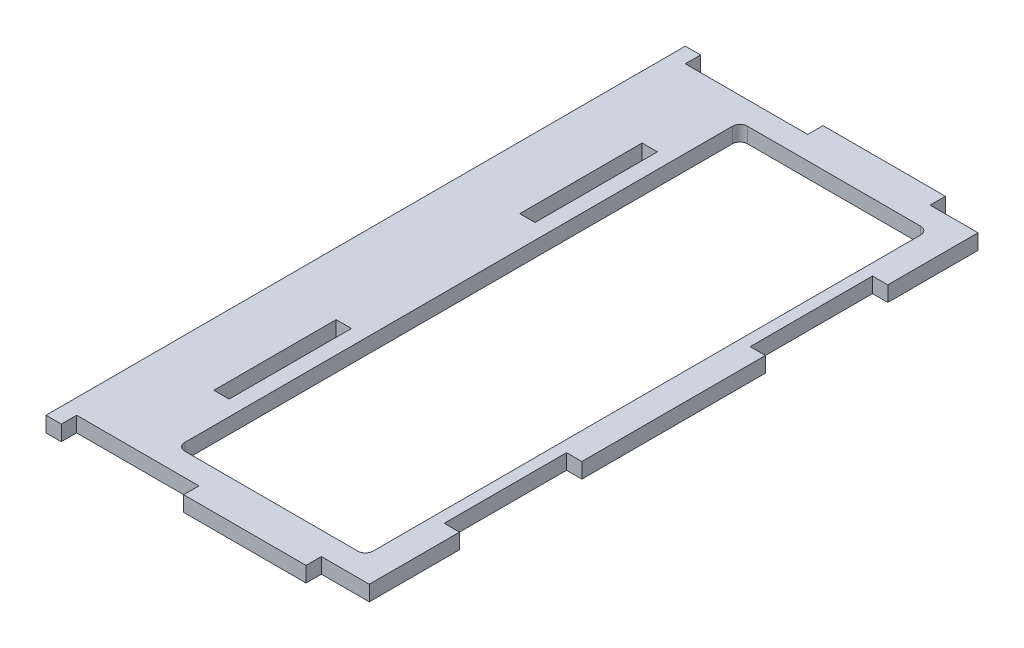
SolidWorks part; units mm, degrees
material "Acrylic (Medium-high impact)"
ref_plane "Front Plane" through (0, 0, 0) normal (0, 0, 1) x (1, 0, 0)
ref_plane "Top Plane" through (0, 0, 0) normal (0, 1, 0) x (1, 0, 0)
ref_plane "Right Plane" through (0, 0, 0) normal (1, 0, 0) x (0, 0, -1)
sketch "Sketch2" plane through (0, 0, 0) normal (0, 1, 0) x (1, 0, 0)
  line L0 (-147.5, 0) -> (147.5, 0) construction
  line L5 (-185, 195.2) -> (185, 195.2) construction
  line L6 (-197.7, -132.7) -> (197.7, -132.7)
  line L13 (110, 120) -> (185, 120)
  line L14 (110, 120) -> (110, -120)
  line L15 (110, -120) -> (185, -120)
  line L16 (185, 120) -> (185, -120)
  line L17 (110, 120) -> (185, -120) construction
  line L18 (110, -120) -> (185, 120) construction
  line L19 (-185, 120) -> (-110, 120)
  line L20 (-185, 120) -> (-185, -120)
  line L21 (-185, -120) -> (-110, -120)
  line L22 (-110, 120) -> (-110, -120)
  line L23 (-185, 120) -> (-110, -120) construction
  line L24 (-185, -120) -> (-110, 120) construction
  line L26 (-110, -37.5) -> (110, -37.5)
  line L27 (-110, -37.5) -> (-110, 37.5)
  line L28 (-110, 37.5) -> (110, 37.5)
  line L29 (110, -37.5) -> (110, 37.5)
  line L30 (-110, -37.5) -> (110, 37.5) construction
  line L31 (-110, 37.5) -> (110, -37.5) construction
  line L41 (-197.7, -132.7) -> (-197.7, 132.7)
  line L42 (-185, 132.7) -> (185, 132.7) construction
  line L43 (197.7, -132.7) -> (197.7, 132.7)
  line L44 (-197.7, -132.7) -> (197.7, 132.7) construction
  line L45 (-197.7, 132.7) -> (197.7, -132.7) construction
  line L47 (-197.7, 132.7) -> (-197.7, 257.7)
  line L48 (-197.7, 257.7) -> (-185, 257.7)
  line L49 (-185, 132.7) -> (-185, 257.7)
  line L51 (185, 132.7) -> (185, 257.7)
  line L52 (185, 257.7) -> (197.7, 257.7)
  line L53 (197.7, 132.7) -> (197.7, 257.7)
  line L54 (-185, 132.7) -> (185, 132.7)
  line L55 (223.1, 132.7) -> (223.1, 283.1)
  line L56 (159.6, 283.1) -> (223.1, 283.1)
  line L57 (159.6, 158.1) -> (159.6, 283.1)
  line L58 (-159.6, 158.1) -> (159.6, 158.1)
  line L59 (-159.6, 158.1) -> (-159.6, 283.1)
  line L60 (-223.1, 283.1) -> (-159.6, 283.1)
  line L61 (-223.1, 132.7) -> (-223.1, 283.1)
  line L62 (-223.1, -158.1) -> (-223.1, 132.7)
  line L63 (-223.1, -158.1) -> (223.1, -158.1)
  line L64 (223.1, -158.1) -> (223.1, 132.7)
  circle A0 centre (0, 308.1) radius 150
  point P2 (0, 0)
  point P13 (147.5, 0)
  point P18 (-147.5, 0)
  point P23 (0, 0)
  point P24 (0, 0)
  point P35 (0, 195.2)
  dimension "D1" = 300
  dimension "D2" = 75
  dimension "D3" = 240
  dimension "D4" = 75
  dimension "D5" = 220
  dimension "D6" = 12.7
  dimension "D7" = 12.7
  dimension "D8" = 12.7
  dimension "D9" = 125
  dimension "D10" = 25.4
sketch "Sketch5" plane through (0, 0, 0) normal (0, 1, 0) x (1, 0, 0)
  line L1 (197.7, -132.7) -> (-197.7, -132.7)
  line L2 (197.7, -132.7) -> (197.7, 132.7)
  line L3 (197.7, 132.7) -> (-197.7, 132.7)
  line L4 (-197.7, -132.7) -> (-197.7, 132.7)
extrude "Boss-Extrude3" add sketch "Sketch5" along normal blind 6.35
sketch "Sketch6" plane through (0, 6.35, 0) normal (0, 1, 0) x (1, 0, 0)
  line L0 (-185, 120) -> (-110, 120) construction
  line L1 (-185, 120) -> (-185, -120) construction
  line L2 (-185, -120) -> (-110, -120) construction
  line L3 (-110, 120) -> (-110, -120) construction
  line L4 (110, 120) -> (110, -120) construction
  line L5 (110, 120) -> (185, 120) construction
  line L6 (185, 120) -> (185, -120) construction
  line L7 (110, -120) -> (185, -120) construction
  line L8 (-185, 120) -> (-110, 120)
  line L9 (-185, 120) -> (-185, -120)
  line L10 (-185, -120) -> (-110, -120)
  line L11 (-110, 120) -> (-110, -120)
  line L12 (110, 120) -> (110, -120)
  line L13 (110, 120) -> (185, 120)
  line L14 (185, 120) -> (185, -120)
  line L15 (110, -120) -> (185, -120)
  line L16 (108.4125, 121.5875) -> (108.4125, -121.5875)
  line L17 (108.4125, -121.5875) -> (186.5875, -121.5875)
  line L18 (186.5875, 121.5875) -> (186.5875, -121.5875)
  line L19 (108.4125, 121.5875) -> (186.5875, 121.5875)
  line L20 (-108.4125, 121.5875) -> (-108.4125, -121.5875)
  line L21 (-186.5875, -121.5875) -> (-108.4125, -121.5875)
  line L22 (-186.5875, 121.5875) -> (-186.5875, -121.5875)
  line L23 (-186.5875, 121.5875) -> (-108.4125, 121.5875)
  dimension "D1" = 1.5875
extrude "Cut-Extrude1" cut sketch "Sketch6" against normal blind 6.35 contours L12 L15 L14 L13 | L19 L16 L17 L18 L15 L12 L13 L14 | L11 L8 L9 L10 | L23 L22 L21 L20 L8 L11 L10 L9
sketch "Sketch7" [suppressed] plane through (0, 6.35, 0) normal (0, 1, 0) x (1, 0, 0)
  arc A0 (191.675, -14.35) -> (191.043, -17.5242) centre (191.675, -16) ccw construction
  arc A1 (192.307, -14.4758) -> (191.675, -14.35) centre (191.675, -16) ccw construction
  arc A2 (191.675, -17.65) -> (192.307, -14.4758) centre (191.675, -16) ccw construction
  arc A3 (191.043, -17.5242) -> (191.675, -17.65) centre (191.675, -16) ccw construction
  arc A4 (191.675, 17.65) -> (191.043, 14.4758) centre (191.675, 16) ccw construction
  arc A5 (192.307, 17.5242) -> (191.675, 17.65) centre (191.675, 16) ccw construction
  arc A6 (191.675, 14.35) -> (192.307, 17.5242) centre (191.675, 16) ccw construction
  arc A7 (191.043, 14.4758) -> (191.675, 14.35) centre (191.675, 16) ccw construction
  arc A8 (103.325, -14.35) -> (102.693, -17.5242) centre (103.325, -16) ccw construction
  arc A9 (103.957, -14.4758) -> (103.325, -14.35) centre (103.325, -16) ccw construction
  arc A10 (103.325, -17.65) -> (103.957, -14.4758) centre (103.325, -16) ccw construction
  arc A11 (102.693, -17.5242) -> (103.325, -17.65) centre (103.325, -16) ccw construction
  arc A12 (103.325, 17.65) -> (102.693, 14.4758) centre (103.325, 16) ccw construction
  arc A13 (103.957, 17.5242) -> (103.325, 17.65) centre (103.325, 16) ccw construction
  arc A14 (103.325, 14.35) -> (103.957, 17.5242) centre (103.325, 16) ccw construction
  arc A15 (102.693, 14.4758) -> (103.325, 14.35) centre (103.325, 16) ccw construction
  arc A16 (-103.325, 17.65) -> (-103.957, 14.4758) centre (-103.325, 16) ccw construction
  arc A17 (-102.693, 17.5242) -> (-103.325, 17.65) centre (-103.325, 16) ccw construction
  arc A18 (-103.325, 14.35) -> (-102.693, 17.5242) centre (-103.325, 16) ccw construction
  arc A19 (-103.957, 14.4758) -> (-103.325, 14.35) centre (-103.325, 16) ccw construction
  arc A20 (-103.325, -14.35) -> (-103.957, -17.5242) centre (-103.325, -16) ccw construction
  arc A21 (-102.693, -14.4758) -> (-103.325, -14.35) centre (-103.325, -16) ccw construction
  arc A22 (-103.325, -17.65) -> (-102.693, -14.4758) centre (-103.325, -16) ccw construction
  arc A23 (-103.957, -17.5242) -> (-103.325, -17.65) centre (-103.325, -16) ccw construction
  arc A24 (-191.675, -14.35) -> (-192.307, -17.5242) centre (-191.675, -16) ccw construction
  arc A25 (-191.043, -14.4758) -> (-191.675, -14.35) centre (-191.675, -16) ccw construction
  arc A26 (-191.675, -17.65) -> (-191.043, -14.4758) centre (-191.675, -16) ccw construction
  arc A27 (-192.307, -17.5242) -> (-191.675, -17.65) centre (-191.675, -16) ccw construction
  arc A28 (-191.675, 14.35) -> (-191.043, 17.5242) centre (-191.675, 16) ccw construction
  arc A29 (-192.307, 14.4758) -> (-191.675, 14.35) centre (-191.675, 16) ccw construction
  arc A30 (-191.675, 17.65) -> (-192.307, 14.4758) centre (-191.675, 16) ccw construction
  arc A31 (-191.043, 17.5242) -> (-191.675, 17.65) centre (-191.675, 16) ccw construction
  circle A32 centre (-61.175, -10) radius 2.25 construction
  circle A33 centre (-61.175, 22) radius 2.25 construction
  circle A34 centre (61.175, 22) radius 2.25 construction
  circle A35 centre (61.175, -10) radius 2.25 construction
  arc A36 (191.675, -14.35) -> (191.043, -17.5242) centre (191.675, -16) ccw construction
  arc A37 (192.307, -14.4758) -> (191.675, -14.35) centre (191.675, -16) ccw construction
  arc A38 (191.675, -17.65) -> (192.307, -14.4758) centre (191.675, -16) ccw construction
  arc A39 (191.043, -17.5242) -> (191.675, -17.65) centre (191.675, -16) ccw construction
  arc A40 (191.675, 17.65) -> (191.043, 14.4758) centre (191.675, 16) ccw construction
  arc A41 (192.307, 17.5242) -> (191.675, 17.65) centre (191.675, 16) ccw construction
  arc A42 (191.675, 14.35) -> (192.307, 17.5242) centre (191.675, 16) ccw construction
  arc A43 (191.043, 14.4758) -> (191.675, 14.35) centre (191.675, 16) ccw construction
  arc A44 (103.325, -14.35) -> (102.693, -17.5242) centre (103.325, -16) ccw construction
  arc A45 (103.957, -14.4758) -> (103.325, -14.35) centre (103.325, -16) ccw construction
  arc A46 (103.325, -17.65) -> (103.957, -14.4758) centre (103.325, -16) ccw construction
  arc A47 (102.693, -17.5242) -> (103.325, -17.65) centre (103.325, -16) ccw construction
  arc A48 (103.325, 17.65) -> (102.693, 14.4758) centre (103.325, 16) ccw construction
  arc A49 (103.957, 17.5242) -> (103.325, 17.65) centre (103.325, 16) ccw construction
  arc A50 (103.325, 14.35) -> (103.957, 17.5242) centre (103.325, 16) ccw construction
  arc A51 (102.693, 14.4758) -> (103.325, 14.35) centre (103.325, 16) ccw construction
  arc A52 (-103.325, 17.65) -> (-103.957, 14.4758) centre (-103.325, 16) ccw construction
  arc A53 (-102.693, 17.5242) -> (-103.325, 17.65) centre (-103.325, 16) ccw construction
  arc A54 (-103.325, 14.35) -> (-102.693, 17.5242) centre (-103.325, 16) ccw construction
  arc A55 (-103.957, 14.4758) -> (-103.325, 14.35) centre (-103.325, 16) ccw construction
  arc A56 (-103.325, -14.35) -> (-103.957, -17.5242) centre (-103.325, -16) ccw construction
  arc A57 (-102.693, -14.4758) -> (-103.325, -14.35) centre (-103.325, -16) ccw construction
  arc A58 (-103.325, -17.65) -> (-102.693, -14.4758) centre (-103.325, -16) ccw construction
  arc A59 (-103.957, -17.5242) -> (-103.325, -17.65) centre (-103.325, -16) ccw construction
  arc A60 (-191.675, -14.35) -> (-192.307, -17.5242) centre (-191.675, -16) ccw construction
  arc A61 (-191.043, -14.4758) -> (-191.675, -14.35) centre (-191.675, -16) ccw construction
  arc A62 (-191.675, -17.65) -> (-191.043, -14.4758) centre (-191.675, -16) ccw construction
  arc A63 (-192.307, -17.5242) -> (-191.675, -17.65) centre (-191.675, -16) ccw construction
  arc A64 (-191.675, 14.35) -> (-191.043, 17.5242) centre (-191.675, 16) ccw construction
  arc A65 (-192.307, 14.4758) -> (-191.675, 14.35) centre (-191.675, 16) ccw construction
  arc A66 (-191.675, 17.65) -> (-192.307, 14.4758) centre (-191.675, 16) ccw construction
  arc A67 (-191.043, 17.5242) -> (-191.675, 17.65) centre (-191.675, 16) ccw construction
  circle A68 centre (-61.175, -10) radius 2.25 construction
  circle A69 centre (-61.175, 22) radius 2.25 construction
  circle A70 centre (61.175, 22) radius 2.25 construction
  circle A71 centre (61.175, -10) radius 2.25 construction
hole_wizard "Ø4.0mm Dowel Hole1" [suppressed] positions "Sketch8" profile "Sketch9" hole size "Ø4.0" standard "ANSI Metric"
sketch "Sketch8" [suppressed] plane through (0, 6.35, 0) normal (0, 1, 0) x (1, 0, 0)
  point P0 (191.675, -16)
  point P3 (191.675, 16)
  point P6 (103.325, -16)
  point P9 (103.325, 16)
  point P12 (-191.675, -16)
  point P15 (-191.675, 16)
  point P18 (-103.325, -16)
  point P21 (-103.325, 16)
  point P24 (-61.175, -10)
  point P27 (-61.175, 22)
  point P30 (61.175, 22)
  point P33 (61.175, -10)
sketch "Sketch9" plane through (191.675, 6.35, 16) normal (1, 0, 0) x (0, 0, 1)
  line L0 (0, 0) -> (0, 6.35)
  line L1 (0, 6.35) -> (2.25, 6.35)
  line L2 (2.25, 6.35) -> (2.25, 0)
  line L5 (2.25, 0) -> (0, 0)
  line L11 (0, -6.35) -> (0, 107.95) construction
  dimension "Thru Hole Dia." = 4.5
  dimension "Thru Hole Depth" = 6.35
sketch "Sketch10" plane through (0, 0, 0) normal (0, -1, 0) x (1, 0, 0)
  line L0 (-191.35, -126.35) -> (191.35, -126.35)
  line L1 (191.35, -126.35) -> (191.35, 126.35)
  line L2 (191.35, 126.35) -> (-191.35, 126.35)
  line L3 (-191.35, 126.35) -> (-191.35, -126.35)
  line L4 (197.7, -132.7) -> (197.7, 132.7)
  line L5 (197.7, 132.7) -> (-197.7, 132.7)
  line L6 (-197.7, 132.7) -> (-197.7, -132.7)
  line L7 (-197.7, -132.7) -> (197.7, -132.7)
  line L8 (197.7, -132.7) -> (197.7, 132.7)
  line L9 (197.7, 132.7) -> (-197.7, 132.7)
  line L10 (-197.7, 132.7) -> (-197.7, -132.7)
  line L11 (-197.7, -132.7) -> (197.7, -132.7)
  line L12 (102.0625, -126.35) -> (102.0625, 126.35)
  line L13 (-102.0625, -126.35) -> (-102.0625, 126.35)
  line L14 (108.4125, -126.35) -> (108.4125, 126.35)
  line L15 (-108.4125, -126.35) -> (-108.4125, 126.35)
  line L16 (108.4125, -121.5875) -> (108.4125, 121.5875) construction
  line L17 (-108.4125, -121.5875) -> (-108.4125, 121.5875) construction
  line L18 (95.7125, -126.35) -> (95.7125, 126.35)
  line L19 (-95.7125, -126.35) -> (-95.7125, 126.35)
  line L20 (197.7, 0) -> (-197.7, 0) construction
  line L21 (102.0625, -88.9) -> (95.7125, -88.9)
  line L22 (102.0625, -88.9) -> (102.0625, -38.1)
  line L23 (102.0625, -38.1) -> (95.7125, -38.1)
  line L24 (95.7125, -88.9) -> (95.7125, -38.1)
  line L25 (102.0625, 38.1) -> (95.7125, 38.1)
  line L26 (102.0625, 38.1) -> (102.0625, 88.9)
  line L27 (102.0625, 88.9) -> (95.7125, 88.9)
  line L28 (95.7125, 38.1) -> (95.7125, 88.9)
  line L29 (-102.0625, -88.9) -> (-95.7125, -88.9)
  line L30 (-102.0625, -88.9) -> (-102.0625, -38.1)
  line L31 (-102.0625, -38.1) -> (-95.7125, -38.1)
  line L32 (-95.7125, -88.9) -> (-95.7125, -38.1)
  line L33 (-95.7125, 88.9) -> (-102.0625, 88.9)
  line L34 (-95.7125, 88.9) -> (-95.7125, 38.1)
  line L35 (-95.7125, 38.1) -> (-102.0625, 38.1)
  line L36 (-102.0625, 88.9) -> (-102.0625, 38.1)
  line L37 (76.2, 126.35) -> (25.4, 126.35)
  line L38 (76.2, 126.35) -> (76.2, 132.7)
  line L39 (76.2, 132.7) -> (25.4, 132.7)
  line L40 (25.4, 126.35) -> (25.4, 132.7)
  line L41 (-25.4, 126.35) -> (-76.2, 126.35)
  line L42 (-25.4, 126.35) -> (-25.4, 132.7)
  line L43 (-25.4, 132.7) -> (-76.2, 132.7)
  line L44 (-76.2, 126.35) -> (-76.2, 132.7)
  line L45 (177.8, 126.35) -> (127, 126.35)
  line L46 (177.8, 126.35) -> (177.8, 132.7)
  line L47 (177.8, 132.7) -> (127, 132.7)
  line L48 (127, 126.35) -> (127, 132.7)
  line L49 (-127, 126.35) -> (-177.8, 126.35)
  line L50 (-127, 126.35) -> (-127, 132.7)
  line L51 (-127, 132.7) -> (-177.8, 132.7)
  line L52 (-177.8, 126.35) -> (-177.8, 132.7)
  line L53 (-127, -132.7) -> (-177.8, -132.7)
  line L54 (-177.8, -126.35) -> (-177.8, -132.7)
  line L55 (-127, -126.35) -> (-177.8, -126.35)
  line L56 (-127, -126.35) -> (-127, -132.7)
  line L57 (-25.4, -132.7) -> (-76.2, -132.7)
  line L58 (-76.2, -126.35) -> (-76.2, -132.7)
  line L59 (-25.4, -126.35) -> (-76.2, -126.35)
  line L60 (-25.4, -126.35) -> (-25.4, -132.7)
  line L61 (76.2, -132.7) -> (25.4, -132.7)
  line L62 (25.4, -126.35) -> (25.4, -132.7)
  line L63 (76.2, -126.35) -> (25.4, -126.35)
  line L64 (76.2, -126.35) -> (76.2, -132.7)
  line L65 (177.8, -132.7) -> (127, -132.7)
  line L66 (127, -126.35) -> (127, -132.7)
  line L67 (177.8, -126.35) -> (127, -126.35)
  line L68 (177.8, -126.35) -> (177.8, -132.7)
  line L69 (191.35, 126.35) -> (197.7, 126.35)
  line L70 (-191.35, 126.35) -> (-197.7, 126.35)
  line L71 (-191.35, -126.35) -> (-197.7, -126.35)
  line L72 (191.35, -126.35) -> (197.7, -126.35)
  line M31 (197.7, -132.7) -> (197.7, 132.7)
  line M32 (197.7, 132.7) -> (-197.7, 132.7)
  line M33 (-197.7, 132.7) -> (-197.7, -132.7)
  line M34 (-197.7, -132.7) -> (197.7, -132.7)
  dimension "D3" = 6.35
  dimension "D4" = 6.35
  dimension "D5" = 6.35
  dimension "D6" = 6.35
  dimension "D7" = 50.8
  dimension "D8" = 50.8
  dimension "D9" = 76.2
  dimension "D10" = 38.1
  dimension "D11" = 50.8
  dimension "D12" = 50.8
  dimension "D13" = 50.8
  dimension "D14" = 25.4
  dimension "D15" = 50.8
  dimension "D16" = 50.8
  dimension "D17" = 50.8
  dimension "D18" = 50.8
  dimension "D1" = 0
  dimension "D2" = 6.35
extrude "Cut-Extrude2" cut sketch "Sketch10" against normal blind 6.35 contours L12 L23 L18 L21 | L12 L27 L18 L25 | L35 L19 L33 L13 | L31 L13 L29 L19 | L2 L69 L8 L46 M32 | L2 L48 L38 M32 | L42 L2 L40 M32 | L50 L2 L44 M32 | L70 L2 L52 M32 M33 | L0 L71 L54 M33 M34 | L58 L0 L56 M34 | L62 L0 L60 M34 | L66 L0 L64 M34 | L72 L0 L68 M34 M31
sketch "Sketch11" plane through (197.7, 0, 0) normal (1, 0, 0) x (0, 0, -1)
  line L0 (-88.9, 0) -> (-38.1, 0) construction
  line L1 (-38.1, 0) -> (-38.1, 6.35) construction
  line L2 (-38.1, 6.35) -> (-88.9, 6.35) construction
  line L3 (-88.9, 6.35) -> (-88.9, 0) construction
  line L4 (38.1, 0) -> (88.9, 0) construction
  line L5 (88.9, 0) -> (88.9, 6.35) construction
  line L6 (88.9, 6.35) -> (38.1, 6.35) construction
  line L7 (38.1, 6.35) -> (38.1, 0) construction
  line L8 (-88.9, 0) -> (-38.1, 0)
  line L9 (-38.1, 0) -> (-38.1, 6.35)
  line L10 (-38.1, 6.35) -> (-88.9, 6.35)
  line L11 (-88.9, 6.35) -> (-88.9, 0)
  line L12 (38.1, 0) -> (88.9, 0)
  line L13 (88.9, 0) -> (88.9, 6.35)
  line L14 (88.9, 6.35) -> (38.1, 6.35)
  line L15 (38.1, 6.35) -> (38.1, 0)
extrude "Cut-Extrude3" cut sketch "Sketch11" against normal blind 6.35
mirror "Mirror1" about plane through (0, 0, 0) normal (1, 0, 0) of "Cut-Extrude3"
sketch "Sketch12" plane through (0, 0, 0) normal (0, -1, 0) x (1, 0, 0)
  line L0 (108.4125, -121.5875) -> (108.4125, 121.5875) construction
  line L1 (186.5875, -121.5875) -> (108.4125, -121.5875)
  line L2 (186.5875, -121.5875) -> (186.5875, -116.825)
  line L3 (186.5875, -116.825) -> (108.4125, -116.825)
  line L4 (108.4125, -121.5875) -> (108.4125, -116.825)
  line L5 (186.5875, -121.5875) -> (186.5875, 121.5875) construction
  line L6 (108.4125, 121.5875) -> (186.5875, 121.5875)
  line L7 (108.4125, 121.5875) -> (108.4125, 116.825)
  line L8 (108.4125, 116.825) -> (186.5875, 116.825)
  line L9 (186.5875, 121.5875) -> (186.5875, 116.825)
  line L10 (-186.5875, -121.5875) -> (-186.5875, 121.5875) construction
  line L11 (-108.4125, 121.5875) -> (-186.5875, 121.5875)
  line L12 (-108.4125, 121.5875) -> (-108.4125, 116.825)
  line L13 (-108.4125, 116.825) -> (-186.5875, 116.825)
  line L14 (-186.5875, 121.5875) -> (-186.5875, 116.825)
  line L15 (-108.4125, -121.5875) -> (-108.4125, 121.5875) construction
  line L16 (-186.5875, -121.5875) -> (-108.4125, -121.5875)
  line L17 (-186.5875, -121.5875) -> (-186.5875, -116.825)
  line L18 (-186.5875, -116.825) -> (-108.4125, -116.825)
  line L19 (-108.4125, -121.5875) -> (-108.4125, -116.825)
  dimension "D1" = 4.7625
extrude "Boss-Extrude4" add sketch "Sketch12" against normal up to surface (6.35 mm away) up to face at (98.8875, 6.35, 63.5)
fillet "Fillet1" radius 3.175 8 edges at (-186.5875, 3.175, 116.825) (-108.4125, 3.175, 116.825) (-186.5875, 3.175, -116.825) (-108.4125, 3.175, -116.825) (108.4125, 3.175, 116.825) (186.5875, 3.175, 116.825) (108.4125, 3.175, -116.825) (186.5875, 3.175, -116.825)
sketch "Sketch13" plane through (0, 0, 0) normal (0, -1, 0) x (1, 0, 0)
  line L1 (69.85, -132.7) -> (-69.85, -132.7)
  line L2 (69.85, -132.7) -> (69.85, 132.7)
  line L3 (69.85, 132.7) -> (-69.85, 132.7)
  line L4 (-69.85, -132.7) -> (-69.85, 132.7)
  line L56 (-197.7, 88.9) -> (-191.35, 88.9)
  line L57 (-191.35, 88.9) -> (-191.35, 38.1)
  line L58 (-191.35, 38.1) -> (-197.7, 38.1)
  line L59 (-197.7, 38.1) -> (-197.7, -38.1)
  line L60 (-197.7, -38.1) -> (-191.35, -38.1)
  line L61 (-191.35, -38.1) -> (-191.35, -88.9)
  line L62 (-191.35, -88.9) -> (-197.7, -88.9)
  line L63 (-197.7, -88.9) -> (-197.7, -126.35)
  line L64 (-197.7, -126.35) -> (-177.8, -126.35)
  line L65 (-177.8, -126.35) -> (-177.8, -132.7)
  line L66 (-177.8, -132.7) -> (-127, -132.7)
  line L67 (-127, -132.7) -> (-127, -126.35)
  line L68 (-127, -126.35) -> (-76.2, -126.35)
  line L69 (-76.2, -126.35) -> (-76.2, -132.7)
  line L70 (-76.2, -132.7) -> (-25.4, -132.7)
  line L71 (-25.4, -132.7) -> (-25.4, -126.35)
  line L72 (-25.4, -126.35) -> (25.4, -126.35)
  line L73 (25.4, -126.35) -> (25.4, -132.7)
  line L74 (25.4, -132.7) -> (76.2, -132.7)
  line L75 (76.2, -132.7) -> (76.2, -126.35)
  line L76 (76.2, -126.35) -> (127, -126.35)
  line L77 (127, -126.35) -> (127, -132.7)
  line L78 (127, -132.7) -> (177.8, -132.7)
  line L79 (177.8, -132.7) -> (177.8, -126.35)
  line L80 (177.8, -126.35) -> (197.7, -126.35)
  line L81 (197.7, -126.35) -> (197.7, -88.9)
  line L82 (197.7, -88.9) -> (191.35, -88.9)
  line L83 (191.35, -88.9) -> (191.35, -38.1)
  line L84 (191.35, -38.1) -> (197.7, -38.1)
  line L85 (197.7, -38.1) -> (197.7, 38.1)
  line L86 (197.7, 38.1) -> (191.35, 38.1)
  line L87 (191.35, 38.1) -> (191.35, 88.9)
  line L88 (191.35, 88.9) -> (197.7, 88.9)
  line L89 (197.7, 88.9) -> (197.7, 126.35)
  line L90 (197.7, 126.35) -> (177.8, 126.35)
  line L91 (177.8, 126.35) -> (177.8, 132.7)
  line L92 (177.8, 132.7) -> (127, 132.7)
  line L93 (127, 132.7) -> (127, 126.35)
  line L94 (127, 126.35) -> (76.2, 126.35)
  line L95 (76.2, 126.35) -> (76.2, 132.7)
  line L96 (76.2, 132.7) -> (25.4, 132.7)
  line L97 (25.4, 132.7) -> (25.4, 126.35)
  line L98 (25.4, 126.35) -> (-25.4, 126.35)
  line L99 (-25.4, 126.35) -> (-25.4, 132.7)
  line L100 (-25.4, 132.7) -> (-76.2, 132.7)
  line L101 (-76.2, 132.7) -> (-76.2, 126.35)
  line L102 (-76.2, 126.35) -> (-127, 126.35)
  line L103 (-127, 126.35) -> (-127, 132.7)
  line L104 (-127, 132.7) -> (-177.8, 132.7)
  line L105 (-177.8, 132.7) -> (-177.8, 126.35)
  line L106 (-177.8, 126.35) -> (-197.7, 126.35)
  line L107 (-197.7, 126.35) -> (-197.7, 88.9)
  line L108 (-197.7, 88.9) -> (-191.35, 88.9)
  line L109 (-191.35, 88.9) -> (-191.35, 38.1)
  line L110 (-191.35, 38.1) -> (-197.7, 38.1)
  line L111 (-197.7, 38.1) -> (-197.7, -38.1)
  line L112 (-197.7, -38.1) -> (-191.35, -38.1)
  line L113 (-191.35, -38.1) -> (-191.35, -88.9)
  line L114 (-191.35, -88.9) -> (-197.7, -88.9)
  line L115 (-197.7, -88.9) -> (-197.7, -126.35)
  line L116 (-197.7, -126.35) -> (-177.8, -126.35)
  line L117 (-177.8, -126.35) -> (-177.8, -132.7)
  line L118 (-177.8, -132.7) -> (-127, -132.7)
  line L119 (-127, -132.7) -> (-127, -126.35)
  line L120 (-127, -126.35) -> (-76.2, -126.35)
  line L121 (-76.2, -126.35) -> (-76.2, -132.7)
  line L122 (-76.2, -132.7) -> (-25.4, -132.7)
  line L123 (-25.4, -132.7) -> (-25.4, -126.35)
  line L124 (-25.4, -126.35) -> (25.4, -126.35)
  line L125 (25.4, -126.35) -> (25.4, -132.7)
  line L126 (25.4, -132.7) -> (76.2, -132.7)
  line L127 (76.2, -132.7) -> (76.2, -126.35)
  line L128 (76.2, -126.35) -> (127, -126.35)
  line L129 (127, -126.35) -> (127, -132.7)
  line L130 (127, -132.7) -> (177.8, -132.7)
  line L131 (177.8, -132.7) -> (177.8, -126.35)
  line L132 (177.8, -126.35) -> (197.7, -126.35)
  line L133 (197.7, -126.35) -> (197.7, -88.9)
  line L134 (197.7, -88.9) -> (191.35, -88.9)
  line L135 (191.35, -88.9) -> (191.35, -38.1)
  line L136 (191.35, -38.1) -> (197.7, -38.1)
  line L137 (197.7, -38.1) -> (197.7, 38.1)
  line L138 (197.7, 38.1) -> (191.35, 38.1)
  line L139 (191.35, 38.1) -> (191.35, 88.9)
  line L140 (191.35, 88.9) -> (197.7, 88.9)
  line L141 (197.7, 88.9) -> (197.7, 126.35)
  line L142 (197.7, 126.35) -> (177.8, 126.35)
  line L143 (177.8, 126.35) -> (177.8, 132.7)
  line L144 (177.8, 132.7) -> (127, 132.7)
  line L145 (127, 132.7) -> (127, 126.35)
  line L146 (127, 126.35) -> (76.2, 126.35)
  line L147 (76.2, 126.35) -> (76.2, 132.7)
  line L148 (76.2, 132.7) -> (25.4, 132.7)
  line L149 (25.4, 132.7) -> (25.4, 126.35)
  line L150 (25.4, 126.35) -> (-25.4, 126.35)
  line L151 (-25.4, 126.35) -> (-25.4, 132.7)
  line L152 (-25.4, 132.7) -> (-76.2, 132.7)
  line L153 (-76.2, 132.7) -> (-76.2, 126.35)
  line L154 (-76.2, 126.35) -> (-127, 126.35)
  line L155 (-127, 126.35) -> (-127, 132.7)
  line L156 (-127, 132.7) -> (-177.8, 132.7)
  line L157 (-177.8, 132.7) -> (-177.8, 126.35)
  line L158 (-177.8, 126.35) -> (-197.7, 126.35)
  line L159 (-197.7, 126.35) -> (-197.7, 88.9)
  dimension "D2" = 6.35
  dimension "D3" = 6.35
  dimension "D1" = 0
extrude "Cut-Extrude4" cut sketch "Sketch13" against normal through all contours L150 L151 L3 L4 L1 L123 L124 L125 L2 L149 | L158 L159 L108 L109 L110 L111 L112 L113 L114 L115 L116 L117 L118 L119 L120 L121 L122 L4 L152 L153 L154 L155 L156 L157
